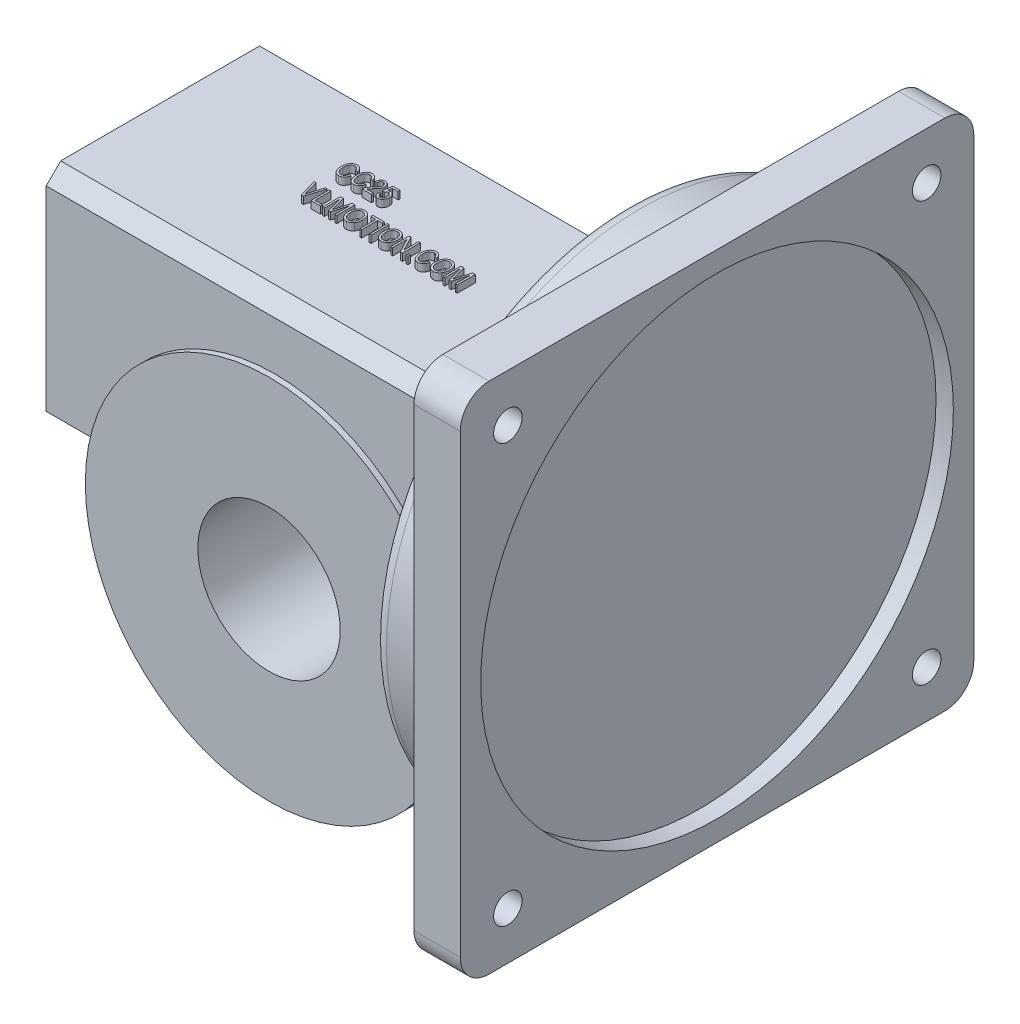
SolidWorks part; units mm, degrees
ref_plane "Front Plane" through (0, 0, 0) normal (0, 0, 1) x (1, 0, 0)
ref_plane "Top Plane" through (0, 0, 0) normal (0, 1, 0) x (1, 0, 0)
ref_plane "Right Plane" through (0, 0, 0) normal (1, 0, 0) x (0, 0, -1)
sketch "Sketch1" plane through (0, 0, 0) normal (0, 0, 1) x (1, 0, 0)
  circle A0 centre (0, 0) radius 32.258
  dimension "D1" = 64.516
extrude "Boss-Extrude1" add sketch "Sketch1" along normal blind 21.0058 and the other way blind 21.0058
sketch "Sketch3" plane through (0, 0, 0) normal (1, 0, 0) x (0, 0, -1)
  line L0 (0, 0) -> (0, 24.892) construction
  line L3 (20.0025, 6.477) -> (20.0025, 43.307)
  line L4 (20.0025, 43.307) -> (-20.0025, 43.307)
  line L5 (-20.0025, 6.477) -> (-20.0025, 43.307)
  line L6 (20.0025, 6.477) -> (-20.0025, 43.307) construction
  line L7 (20.0025, 43.307) -> (-20.0025, 6.477) construction
  arc A1 (-20.0025, 6.477) -> (20.0025, 6.477) centre (0, 24.892) ccw
  dimension "D3" = 36.83
  dimension "D1" = 24.892
  dimension "D2" = 40.005
extrude "Boss-Extrude2" add sketch "Sketch3" against normal blind 40.132 and the other way blind 41.656
sketch "Sketch5" plane through (41.656, 0, 0) normal (1, 0, 0) x (0, 0, -1)
  line L0 (0, 0) -> (0, 24.892) construction
  circle A0 centre (0, 24.892) radius 44.577
  dimension "D1" = 89.154
extrude "Boss-Extrude3" add sketch "Sketch5" along normal blind 7.874
sketch "Sketch6" plane through (49.53, 0, 0) normal (1, 0, 0) x (0, 0, -1)
  line L1 (-45.085, 69.977) -> (45.085, 69.977)
  line L2 (-45.085, 69.977) -> (-45.085, -20.193)
  line L3 (-45.085, -20.193) -> (45.085, -20.193)
  line L4 (45.085, 69.977) -> (45.085, -20.193)
  line L5 (-45.085, 69.977) -> (45.085, -20.193) construction
  line L6 (-45.085, -20.193) -> (45.085, 69.977) construction
  point P0 (0, 24.892)
  dimension "D1" = 90.17
  dimension "D2" = 90.17
extrude "Boss-Extrude4" add sketch "Sketch6" along normal blind 8.128
sketch "Sketch7" plane through (57.658, 0, 0) normal (1, 0, 0) x (0, 0, -1)
  line L0 (-45.085, 24.892) -> (45.085, 24.892) construction
  line L1 (-45.085, 69.977) -> (-45.085, -20.193) construction
  line L2 (45.085, -20.193) -> (45.085, 69.977) construction
  line L3 (36.8099, 61.7019) -> (-36.7292, -11.8372) construction
  line L4 (36.8099, -11.9179) -> (-36.7292, 61.6212) construction
  line L5 (0, 69.977) -> (0, -20.193) construction
  line L6 (45.085, 69.977) -> (-45.085, 69.977) construction
  line L7 (-45.085, -20.193) -> (45.085, -20.193) construction
  circle A0 centre (0, 24.892) radius 51.943 construction
  dimension "D1" = 103.886
  dimension "D3" = 45
hole_wizard "M6 Tapped Hole1" positions "Sketch13" profile "Sketch12" tap size "M6" standard "DIN"
sketch "Sketch13" plane through (57.658, 0, 0) normal (1, 0, 0) x (0, 0, -1)
  point P0 (-36.7292, 61.6212)
  point P3 (36.8099, 61.7019)
  point P6 (36.8099, -11.9179)
  point P9 (-36.7292, -11.8372)
sketch "Sketch12" plane through (57.658, 61.6212, 36.7292) normal (0, 1, 0) x (0, 0, -1)
  line L0 (0, 0) -> (0, 18.5202)
  line L1 (0, 18.5202) -> (2.5, 17.018)
  line L2 (2.5, 17.018) -> (2.5, 0)
  line L5 (2.5, 0) -> (0, 0)
  line L10 (0, 18.5202) -> (-2.5, 17.018) construction
  line L11 (0, -6.35) -> (0, 107.95) construction
  dimension "Tap Drill Dia." = 5
  dimension "Tap Drill Depth" = 17.018
  dimension "Drill Angle" = 118
cosmetic thread "Hole Thread1" parameters "D1"=8.128, "D2"=6
cosmetic thread "Hole Thread2" parameters "D1"=8.128, "D2"=6
cosmetic thread "Hole Thread3" parameters "D1"=8.128, "D2"=6
cosmetic thread "Hole Thread4" parameters "D1"=8.128, "D2"=6
sketch "Sketch10" plane through (57.658, 0, 0) normal (1, 0, 0) x (0, 0, -1)
  line L0 (-45.085, 24.892) -> (45.085, 24.892) construction
  circle A0 centre (0, 24.892) radius 41.5
  dimension "D1" = 83
extrude "Cut-Extrude1" cut sketch "Sketch10" against normal blind 3.048
sketch "Sketch11" plane through (54.61, 0, 0) normal (1, 0, 0) x (0, 0, -1)
  circle A0 centre (0, 24.892) radius 39.497
  dimension "D1" = 78.994
extrude "Cut-Extrude2" [suppressed] cut sketch "Sketch11" against normal blind 7.112
fillet "Fillet1" radius 5.08 4 edges at (53.594, -20.193, -45.085) (53.594, -20.193, 45.085) (53.594, 69.977, -45.085) (53.594, 69.977, 45.085)
chamfer "Chamfer1" distance 2.54 angle 45 2 edges at (0.762, 43.307, -20.0025) (0.762, 43.307, 20.0025)
fillet "Fillet2" radius 2.54 1 edges at (41.656, 24.892, -44.577)
sketch "Sketch14" plane through (0, 0, 21.0058) normal (0, 0, 1) x (1, 0, 0)
  circle A0 centre (0, 0) radius 12.5
  dimension "D1" = 25
extrude "Cut-Extrude3" cut sketch "Sketch14" against normal through all
sketch "Sketch15" plane through (0, 43.307, 0) normal (0, 1, 0) x (1, 0, 0)
  text T0 "CC25\r\nVLMOTION.COM" font "Arial Narrow" height 3.175
  point P1 (0, 0)
  point P2 (-13.5881, 3.4549)
extrude "Boss-Extrude5" add sketch "Sketch15" along normal blind 1.27
